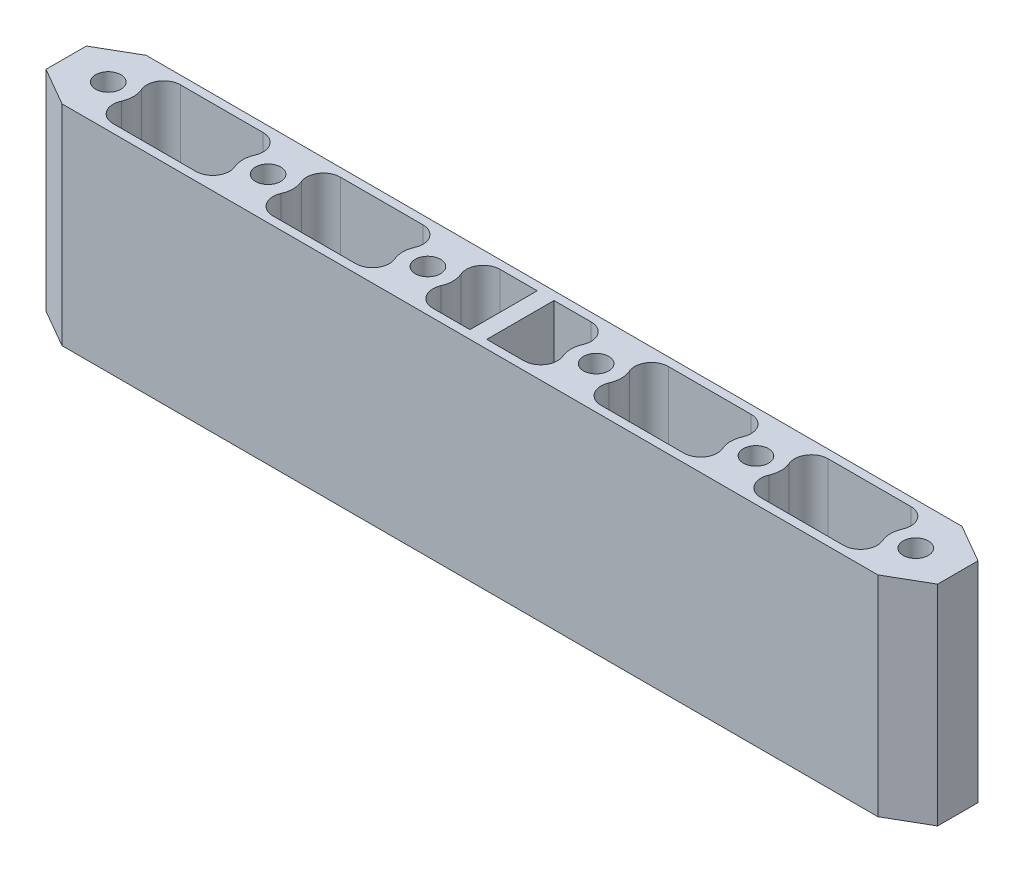
SolidWorks part; units mm, degrees
ref_plane "Front Plane" through (0, 0, 0) normal (0, 0, 1) x (1, 0, 0)
ref_plane "Top Plane" through (0, 0, 0) normal (0, 1, 0) x (1, 0, 0)
ref_plane "Right Plane" through (0, 0, 0) normal (1, 0, 0) x (0, 0, -1)
sketch "Sketch1" plane through (0, 0, 0) normal (0, 1, 0) x (1, 0, 0)
  line L0 (-159, 0) -> (53, 0) construction
  line L1 (-159, -10) -> (53, -10)
  line L2 (-53, -10) -> (-53, 10)
  line L3 (-159, 10) -> (53, 10)
  line L4 (53, -10) -> (53, 10)
  line L5 (-53, -10) -> (53, 10) construction
  line L6 (-53, 10) -> (53, -10) construction
  line L7 (-159, 8) -> (53, 8)
  line L8 (-159, -8) -> (53, -8)
  line L9 (-51, 10) -> (-51, -10)
  line L10 (-55, 10) -> (-55, -10)
  line L11 (-53, 10) -> (-159, -10) construction
  line L12 (-53, -10) -> (-159, 10) construction
  line L13 (-159, -10) -> (-159, 10)
  line L14 (53, 4.8) -> (43.99, 10)
  line L15 (-159, 4.8) -> (-149.99, 10)
  line L16 (53, -4.8) -> (43.99, -10)
  line L17 (-159, -4.8) -> (-149.99, -10)
  circle A0 centre (-33, 0) radius 3
  circle A1 centre (5, 0) radius 3
  circle A2 centre (43, 0) radius 3
  circle A3 centre (-33, 0) radius 6
  circle A4 centre (5, 0) radius 6
  circle A5 centre (43, 0) radius 6
  circle A6 centre (-42.1652, 4) radius 4
  circle A7 centre (-23.8348, 4) radius 4
  circle A8 centre (-4.1652, 4) radius 4
  circle A9 centre (14.1652, 4) radius 4
  circle A10 centre (33.8348, 4) radius 4
  circle A11 centre (33.8348, -4) radius 4
  circle A12 centre (14.1652, -4) radius 4
  circle A13 centre (-4.1652, -4) radius 4
  circle A14 centre (-23.8348, -4) radius 4
  circle A15 centre (-42.1652, -4) radius 4
  circle A16 centre (-63.8348, -4) radius 4
  circle A17 centre (-82.1652, -4) radius 4
  circle A18 centre (-101.8348, -4) radius 4
  circle A19 centre (-120.1652, -4) radius 4
  circle A20 centre (-139.8348, -4) radius 4
  circle A21 centre (-139.8348, 4) radius 4
  circle A22 centre (-120.1652, 4) radius 4
  circle A23 centre (-101.8348, 4) radius 4
  circle A24 centre (-82.1652, 4) radius 4
  circle A25 centre (-63.8348, 4) radius 4
  circle A26 centre (-149, 0) radius 6
  circle A27 centre (-111, 0) radius 6
  circle A28 centre (-73, 0) radius 6
  circle A29 centre (-149, 0) radius 3
  circle A30 centre (-111, 0) radius 3
  circle A31 centre (-73, 0) radius 3
  point P0 (0, 0)
  point P3 (-106, 0)
  point P48 (-53, 0)
  point P78 (-53, -8)
  point P79 (-53, 8)
  dimension "D2" = 6
  dimension "D3" = 20
  dimension "D4" = 38
  dimension "D5" = 38
  dimension "D7" = 3
  dimension "D1" = 10
  dimension "D6" = 10
  dimension "D8" = 2
  dimension "D9" = 2
  dimension "D10" = 5.2
  dimension "D11" = 9.01
  dimension "D12" = 10.4029
extrude "Boss-Extrude1" add sketch "Sketch1" along normal blind 49.8 contours L2 L7 L4 L3 | L8 L2 L1 L4 | A3 A0 | A7 L7 A6 A3 | A3 A15 L8 A14 | A9 L7 A8 A4 | A4 A13 L8 A12 | A4 A1 | A5 A11 L8 L4 L7 A10 | A5 A2 | L9 L7 L2 L8 | L9 L3 L2 L7 | L9 L8 L2 L1 | L7 L10 L8 L2 | L8 L10 L1 L2 | L3 L10 L7 L2 | L13 L7 L10 L3 | L13 L1 L10 L8 | A28 A31 | A16 A28 A17 L8 | A24 A28 A25 L7 | A22 A27 A23 L7 | A27 A30 | A18 A27 A19 L8 | A20 A26 A21 L7 L13 L8 | A26 A29
